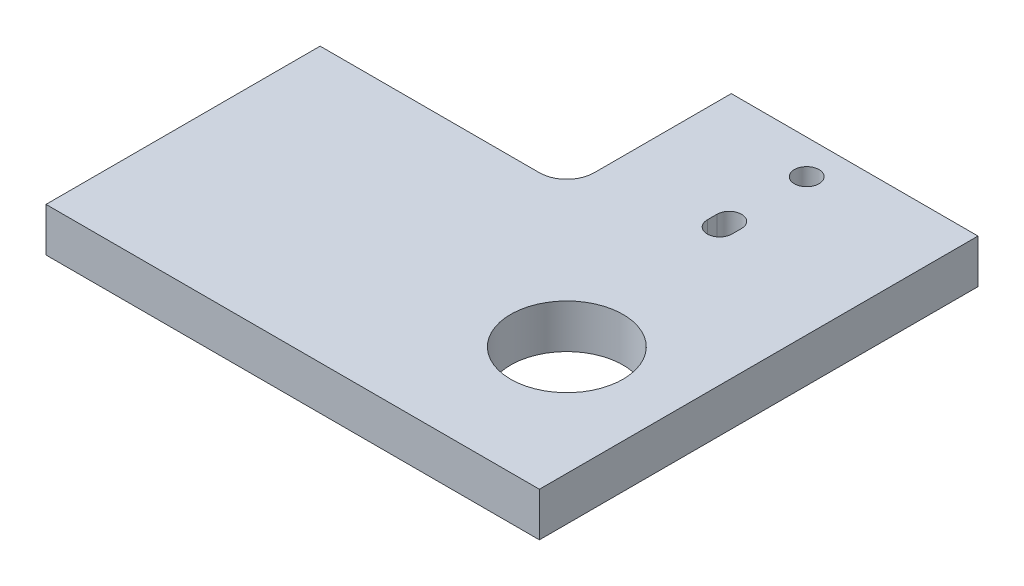
SolidWorks part; units mm, degrees
ref_plane "Front Plane" through (0, 0, 0) normal (0, 0, 1) x (1, 0, 0)
ref_plane "Top Plane" through (0, 0, 0) normal (0, 1, 0) x (1, 0, 0)
ref_plane "Right Plane" through (0, 0, 0) normal (1, 0, 0) x (0, 0, -1)
sketch "Sketch1" plane through (0, 0, 0) normal (0, 1, 0) x (1, 0, 0)
  line L0 (1, 10) -> (1, 16)
  line L1 (0, 0) -> (10, 0)
  line L3 (1, 16) -> (10, 16)
  line L4 (10, 16) -> (10, 8)
  line L5 (1, 10) -> (-8, 10)
  line L7 (0, 0) -> (-8, 0)
  line L8 (10, 8) -> (10, 0)
  line L9 (-8, 10) -> (-8, 0)
  circle A2 centre (6, 5) radius 2.05
  point P1 (5.5, 16)
  dimension "D3" = 9
  dimension "D8" = 4
  dimension "D7" = 18
  dimension "D9" = 8
  dimension "D10" = 4.1
  dimension "D2" = 5
  dimension "D4" = 16
  dimension "D5" = 10
  dimension "D6" = 10
extrude "Boss-Extrude1" add sketch "Sketch1" along normal blind 1.6
sketch "Sketch2" plane through (0, 1.6, 0) normal (0, 1, 0) x (1, 0, 0)
  line L0 (4.55, 11.575) -> (4.55, 11.925)
  line L1 (10, 16) -> (1, 16) construction
  line L2 (5.45, 11.925) -> (5.45, 11.575)
  line L3 (4.55, 11.75) -> (5.45, 11.75) construction
  line L4 (1, 16) -> (1, 10) construction
  circle A0 centre (5, 14.75) radius 0.45
  arc A1 (5.45, 11.925) -> (4.55, 11.925) centre (5, 11.925) ccw
  arc A2 (4.55, 11.575) -> (5.45, 11.575) centre (5, 11.575) ccw
  dimension "D1" = 0.9
  dimension "D2" = 0.35
  dimension "D3" = 1.25
  dimension "D4" = 3
  dimension "D5" = 0.45
  dimension "D6" = 4
extrude "Cut-Extrude1" cut sketch "Sketch2" against normal through all
fillet "Fillet1" radius 1 1 edges at (1, 0.8, -10)
